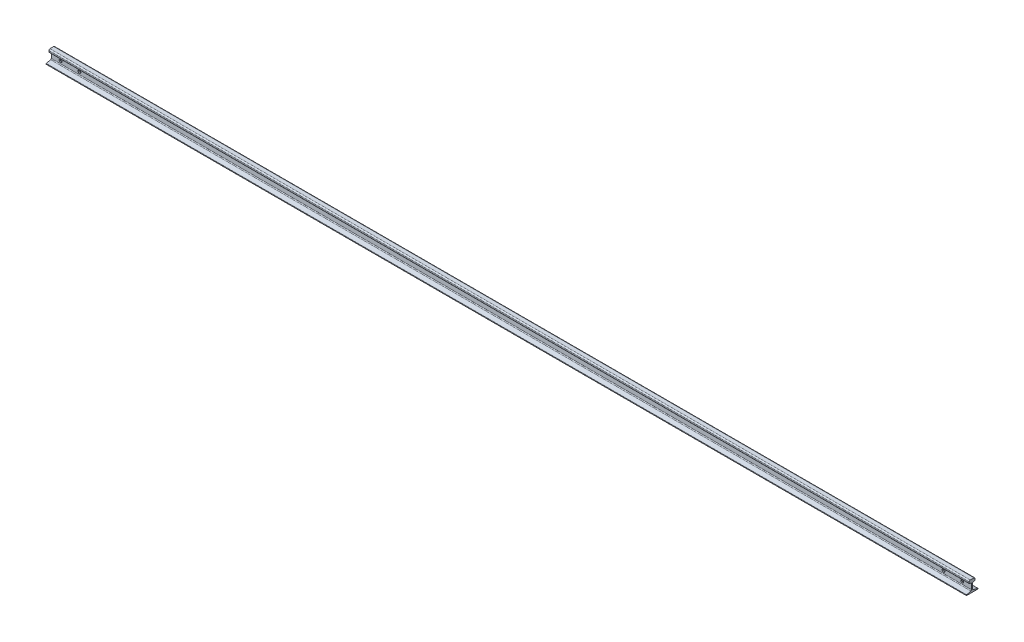
SolidWorks part; units mm, degrees
ref_plane "Front" through (0, 0, 0) normal (0, 0, 1) x (1, 0, 0)
ref_plane "Top" through (0, 0, 0) normal (0, 1, 0) x (1, 0, 0)
ref_plane "Right" through (0, 0, 0) normal (1, 0, 0) x (0, 0, -1)
other "Configuration Table"
sketch "Sketch1" plane through (0, 0, 0) normal (1, 0, 0) x (0, 0, -1)
  line L1 (16.05, 63.0771) -> (16.05, 49.0444)
  line L2 (16.05, 49.0444) -> (2.95, 46.02)
  line L3 (2.95, 46.02) -> (2.95, 10.3)
  line L4 (2.95, 10.3) -> (31.75, 3.651)
  line L5 (31.75, 3.651) -> (31.75, 0)
  line L6 (31.75, 0) -> (-31.75, 0)
  line L7 (0, 0) -> (0, 92.0717) construction
  line L8 (-31.75, 3.651) -> (-31.75, 0)
  line L9 (-2.95, 10.3) -> (-31.75, 3.651)
  line L10 (-2.95, 46.02) -> (-2.95, 10.3)
  line L11 (-16.05, 49.0444) -> (-2.95, 46.02)
  line L12 (-16.05, 63.0771) -> (-16.05, 49.0444)
  arc A0 (-16.05, 63.0771) -> (16.05, 63.0771) centre (0, -241.3) cw
  dimension "D5" = 304.8
  dimension "D6" = 63.5
  dimension "D1" = 63.5
  dimension "D2" = 13
  dimension "D3" = 5.9
  dimension "D4" = 10.3
  dimension "D7" = 32.1
  dimension "D8" = 35.72
  dimension "D9" = 13
extrude "Base" add sketch "Sketch1" along normal blind 5000
fillet "Fillet1" radius 6.35 2 edges at (2500, 63.0771, -16.05) (2500, 63.0771, 16.05)
fillet "Fillet2" radius 4.76 4 edges at (2500, 46.02, -2.95) (2500, 10.3, -2.95) (2500, 46.02, 2.95) (2500, 10.3, 2.95)
fillet "Fillet3" radius 1.59 6 edges at (2500, 49.0444, 16.05) (2500, 0, -31.75) (2500, 3.651, -31.75) (2500, 0, 31.75) (2500, 3.651, 31.75) (2500, 49.0444, -16.05)
sketch "Sketch2" plane through (416.8909, -3.4733, 2.95) normal (0, 0, 1) x (1, 0, 0)
  line L0 (-416.8909, 45.707) -> (-416.8909, 17.5595) construction
  line L1 (-416.8909, 66.8122) -> (4583.1091, 66.8122) construction
  line L3 (4583.1091, 45.707) -> (4583.1091, 17.5595) construction
  circle A0 centre (-366.0909, 31.4722) radius 8
  circle A1 centre (-264.4909, 31.4722) radius 8
  circle A2 centre (4430.7091, 31.4722) radius 8
  circle A3 centre (4532.3091, 31.4722) radius 8
  dimension "D3" = 16
  dimension "D4" = 101.6
  dimension "D6" = 101.6
  dimension "D5" = 50.8
  dimension "D1" = 35.34
  dimension "D2" = 50.8
extrude "Cut-Extrude1" cut sketch "Sketch2" against normal through all
equation "\"D5@Sketch2\" = \"D2@Sketch2\""
equation "\"D6@Sketch2\" = \"D4@Sketch2\""
